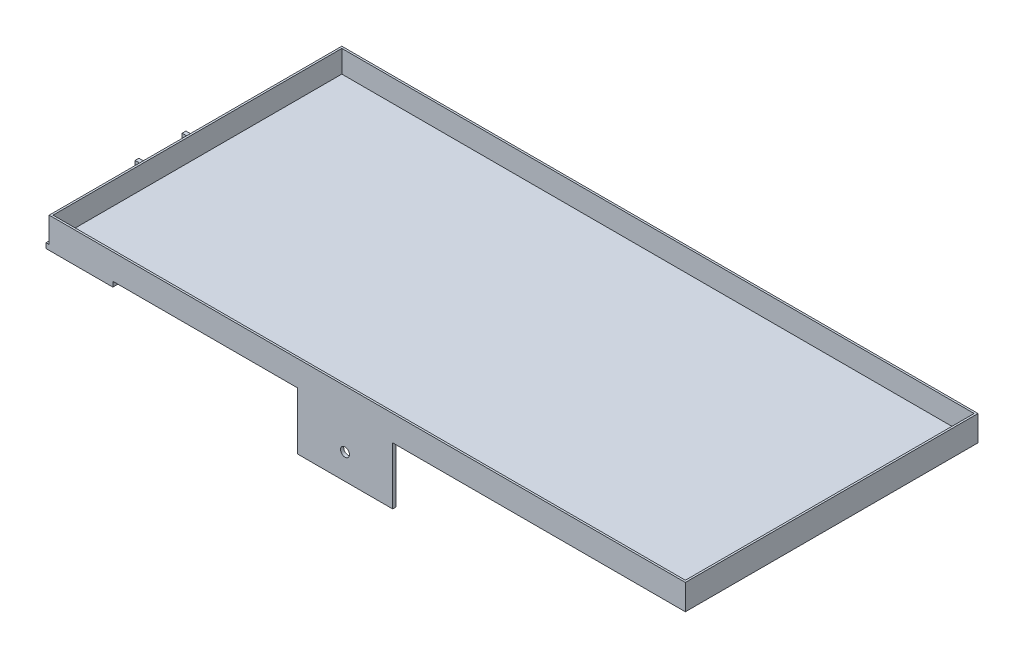
SolidWorks part; units mm, degrees
material "Alliage 1060"
ref_plane "Plan de face" through (0, 0, 0) normal (0, 0, 1) x (1, 0, 0)
ref_plane "Plan de dessus" through (0, 0, 0) normal (0, 1, 0) x (1, 0, 0)
ref_plane "Plan de droite" through (0, 0, 0) normal (1, 0, 0) x (0, 0, -1)
sketch "Esquisse2" plane through (0, 0, 0) normal (0, 1, 0) x (1, 0, 0)
  line L1 (0, -230) -> (1000, -230)
  line L2 (0, -230) -> (0, 230)
  line L3 (0, 230) -> (1000, 230)
  line L4 (1000, -230) -> (1000, 230)
  dimension "D1" = 460
  dimension "D2" = 1000
extrude "Boss.-Extru.1" add sketch "Esquisse2" along normal blind 40
sketch "Esquisse3" plane through (0, 0, 0) normal (0, -1, 0) x (1, 0, 0)
  line L0 (0, 230) -> (1000, 230) construction
  line L1 (390, 230) -> (540, 230)
  line L2 (390, 230) -> (390, 225)
  line L3 (390, 225) -> (540, 225)
  line L4 (540, 230) -> (540, 225)
  line L5 (0, -230) -> (0, 230) construction
  dimension "D1" = 5
  dimension "D2" = 390
  dimension "D3" = 150
extrude "Boss.-Extru.2" add sketch "Esquisse3" along normal blind 90
sketch "Esquisse4" plane through (0, 0, 230) normal (0, 0, 1) x (1, 0, 0)
  line L0 (540, 0) -> (1000, 0) construction
  line L1 (390, -90) -> (390, 0) construction
  circle A0 centre (465, -50) radius 7
  dimension "D1" = 14
  dimension "D2" = 50
  dimension "D3" = 75
extrude "Enlèv. mat.-Extru.1" cut sketch "Esquisse4" against normal up to next
sketch "Esquisse5" plane through (0, 0, 0) normal (0, -1, 0) x (1, 0, 0)
  line L0 (0, 230) -> (390, 230) construction
  line L1 (100, 230) -> (-5, 230)
  line L2 (100, 230) -> (100, -230)
  line L3 (100, -230) -> (-5, -230)
  line L4 (-5, 230) -> (-5, -230)
  line L5 (1000, -230) -> (0, -230) construction
  line L6 (0, -230) -> (0, 230) construction
  dimension "D1" = 5
  dimension "D2" = 105
extrude "Boss.-Extru.3" add sketch "Esquisse5" along normal blind 8
sketch "Esquisse6" plane through (0, -8, 0) normal (0, -1, 0) x (1, 0, 0)
  line L1 (-55, 40) -> (100, 40)
  line L2 (-55, 40) -> (-55, 34)
  line L3 (-55, 34) -> (100, 34)
  line L4 (100, 40) -> (100, 34)
  line L5 (100, -230) -> (100, 230) construction
  line L6 (-5, 230) -> (-5, -230) construction
  dimension "D1" = 6
  dimension "D2" = 40
  dimension "D3" = 50
extrude "Boss.-Extru.4" add sketch "Esquisse6" along normal blind 40
chamfer "Chanfrein1" distance 30 distance2 30 1 edges at (100, -48, 37)
fillet "Congé1" radius 35 1 edges at (-55, -48, 37)
sketch "Esquisse7" plane through (0, 0, 40) normal (0, 0, 1) x (1, 0, 0)
  line L0 (100, 0) -> (390, 0) construction
  line L1 (0, 40) -> (0, 0) construction
  circle A0 centre (-40, -20) radius 7
  dimension "D1" = 14
  dimension "D2" = 20
  dimension "D3" = 40
extrude "Enlèv. mat.-Extru.2" cut sketch "Esquisse7" against normal up to next
sketch "Esquisse8" plane through (0, 40, 0) normal (0, 1, 0) x (1, 0, 0)
  line L0 (1000, 230) -> (0, 230) construction
  line L1 (997, -227) -> (3, -227)
  line L2 (997, -227) -> (997, 227)
  line L3 (997, 227) -> (3, 227)
  line L4 (3, -227) -> (3, 227)
  line L5 (0, -230) -> (1000, -230) construction
  line L6 (0, 230) -> (0, -230) construction
  line L7 (1000, -230) -> (1000, 230) construction
  dimension "D1" = 3
  dimension "D2" = 3
  dimension "D3" = 3
  dimension "D4" = 3
extrude "Enlèv. mat.-Extru.3" cut sketch "Esquisse8" against normal blind 35
ref_plane "Plan1" through (0, 0, 0) normal (0, 0, -1) x (-1, 0, 0)
mirror "Symétrie1" about plane through (0, 0, 0) normal (0, 0, -1) of "Congé1", "Boss.-Extru.4", "Chanfrein1", "Enlèv. mat.-Extru.2", "Boss.-Extru.2", "Enlèv. mat.-Extru.1"
sketch "Esquisse9" plane through (0, 0, 0) normal (0, -1, 0) x (1, 0, 0)
  line L0 (1000, 230) -> (100, -230) construction
